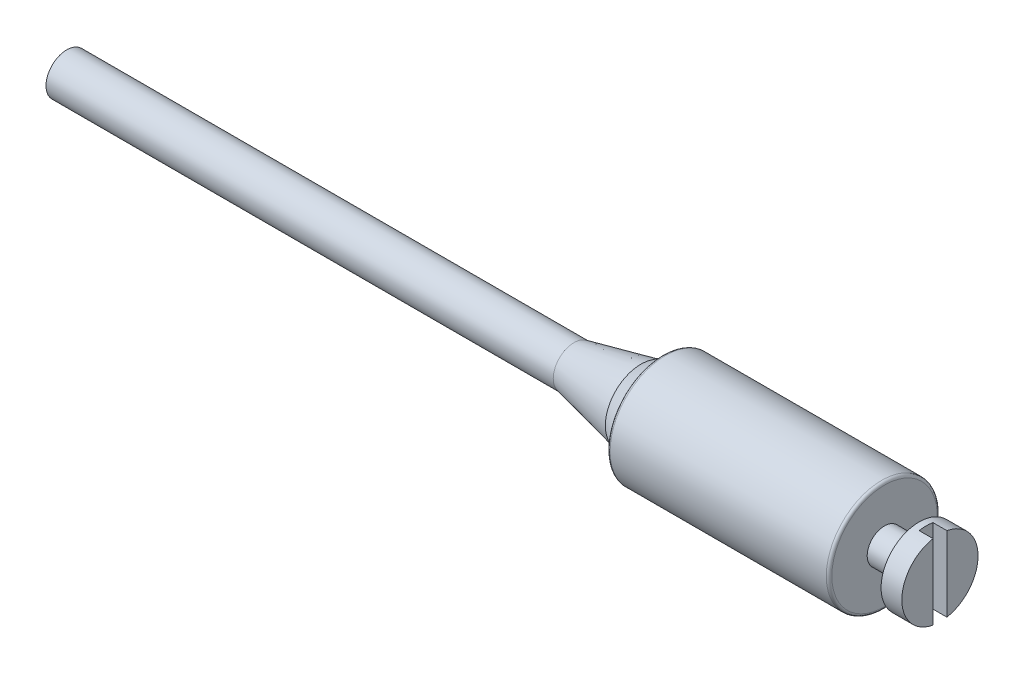
SolidWorks part; units mm, degrees
ref_plane "Front Plane" through (0, 0, 0) normal (0, 0, 1) x (1, 0, 0)
ref_plane "Top Plane" through (0, 0, 0) normal (0, 1, 0) x (1, 0, 0)
ref_plane "Right Plane" through (0, 0, 0) normal (1, 0, 0) x (0, 0, -1)
sketch "Sketch1" plane through (0, 0, 0) normal (0, 0, 1) x (1, 0, 0)
  line L0 (-6.4026, 1.5) -> (-43, 1.5)
  line L1 (-43, 1.5) -> (-43, 0)
  line L2 (-43, 0) -> (16, 0)
  line L3 (16, 1.25) -> (16, 4)
  line L4 (16, 4) -> (0, 4)
  line L5 (0, 4) -> (0, 3.6033)
  line L6 (16, 0) -> (20, 0)
  line L7 (20, 0) -> (20, 2.75)
  line L8 (20, 2.75) -> (18.5, 2.75)
  line L9 (18.5, 2.75) -> (18.5, 1.25)
  line L10 (18.5, 1.25) -> (16, 1.25)
  line L11 (0, 1.5) -> (0, 0) construction
  line L12 (-6.4026, 1.5) -> (-1.5818, 2.561)
  line L13 (-1.5818, 2.561) -> (0, 3.6033)
  dimension "D1" = 1.5
  dimension "D2" = 4
  dimension "D3" = 16
  dimension "D4" = 4
  dimension "D5" = 2.5
  dimension "D6" = 1.25
  dimension "D7" = 2.75
  dimension "D8" = 63
revolve "Revolve1" add sketch "Sketch1" angle 360 about L2
fillet "Fillet1" radius 0.2 2 edges at (16, 0, 4) (0, 0, 4)
sketch "Sketch2" plane through (20, 0, 0) normal (1, 0, 0) x (0, 0, -1)
  line L1 (-0.5, -2.9926) -> (0.5, -2.9926)
  line L2 (-0.5, -2.9926) -> (-0.5, 3.1093)
  line L3 (-0.5, 3.1093) -> (0.5, 3.1093)
  line L4 (0.5, -2.9926) -> (0.5, 3.1093)
  dimension "D1" = 1
  dimension "D2" = 0.5
extrude "Cut-Extrude1" cut sketch "Sketch2" against normal blind 1
